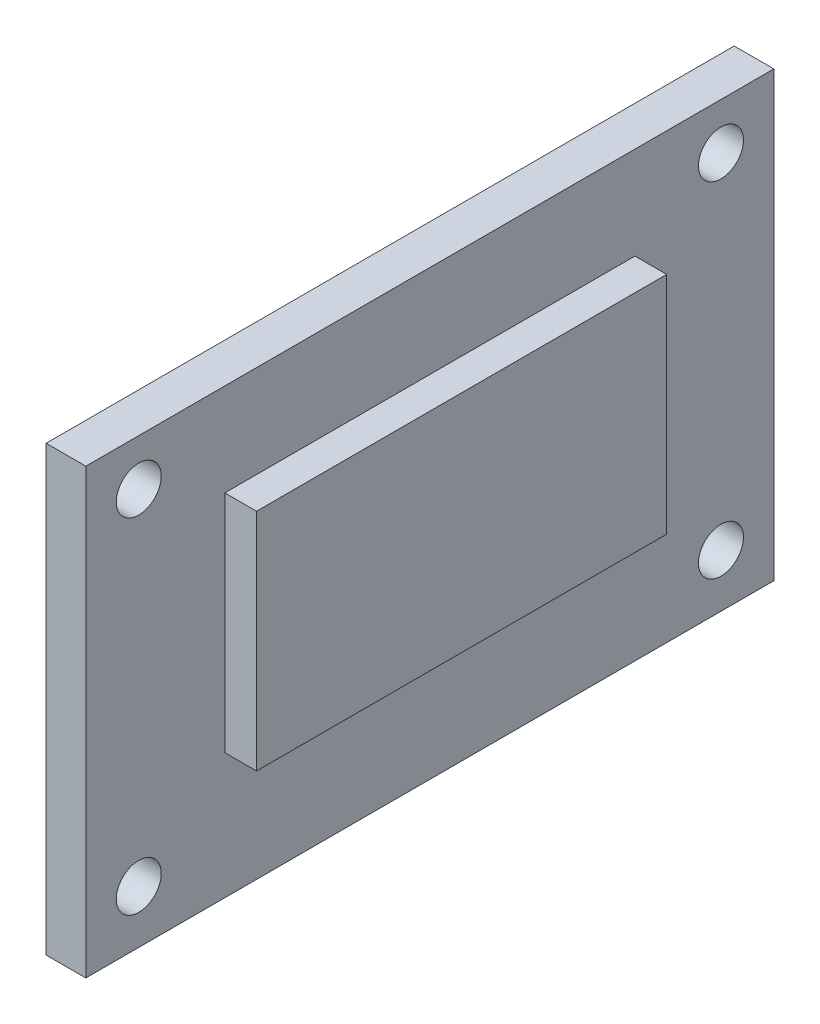
SolidWorks part; units mm, degrees
ref_plane "Front Plane" through (0, 0, 0) normal (0, 0, 1) x (1, 0, 0)
ref_plane "Top Plane" through (0, 0, 0) normal (0, 1, 0) x (1, 0, 0)
ref_plane "Right Plane" through (0, 0, 0) normal (1, 0, 0) x (0, 0, -1)
ref_plane "PXm75_4" through (-75.4, 0, 0) normal (1, 0, 0) x (0, 0, -1)
sketch "Sketch1" plane through (-75.4, 0, 0) normal (1, 0, 0) x (0, 0, -1)
  line L0 (-90, -27) -> (-38, -27)
  line L1 (-38, -27) -> (-38, 6.5)
  line L2 (-38, 6.5) -> (-90, 6.5)
  line L3 (-90, 6.5) -> (-90, -27)
extrude "Cover Plate" add sketch "Sketch1" along normal blind 3
ref_plane "PXm72_41" through (-72.41, 0, 0) normal (1, 0, 0) x (0, 0, -1)
sketch "Sketch2" plane through (-72.41, 0, 0) normal (1, 0, 0) x (0, 0, -1)
  line L0 (-79.5, -17.5) -> (-48.5, -17.5)
  line L1 (-48.5, -17.5) -> (-48.5, -0.5)
  line L2 (-48.5, -0.5) -> (-79.5, -0.5)
  line L3 (-79.5, -0.5) -> (-79.5, -17.5)
extrude "Locating Plug" add sketch "Sketch2" along normal blind 2.41
ref_plane "PXm76_4" through (-76.4, 0, 0) normal (1, 0, 0) x (0, 0, -1)
sketch "Sketch3" plane through (-76.4, 0, 0) normal (1, 0, 0) x (0, 0, -1)
  circle A0 centre (-86, -23) radius 1.7
  circle A1 centre (-86, 3) radius 1.7
  circle A2 centre (-42, -23) radius 1.7
  circle A3 centre (-42, 3) radius 1.7
extrude "Screw Holes" cut sketch "Sketch3" along normal blind 5
equation "\"BOARD_REAR\" = 86.0"
equation "\"BOARD_FRONT\" = 41.0"
equation "\"BOARD_END\" = 22.0"
equation "\"BOARD_ANGLED\" = 30.0"
equation "\"BOARD_DEPTH\" = 41.8431"
equation "\"PCB_T\" = 1.6"
equation "\"ABOVE_PCB\" = 14.0"
equation "\"BELOW_PCB\" = 6.0"
equation "\"MID_PARTS_H\" = 9.0"
equation "\"BOARD_HOLE_PILOT\" = 1.6"
equation "\"J2_X\" = 19.0"
equation "\"DUPONT_DROP\" = 14.0"
equation "\"BEND_R\" = 5.0"
equation "\"BOARD_GAP\" = 3.0"
equation "\"TOF_FOV\" = 25.0"
equation "\"TOF_MARGIN_DEG\" = 5.0"
equation "\"TOF_WIN_MARGIN\" = 1.0"
equation "\"TOF_Z\" = 9.0"
equation "\"TOF_SIDE_BEARING\" = 90.0"
equation "\"TOF_CONE_LEN\" = 70.0"
equation "\"CAM_W\" = 29.2"
equation "\"CAM_H\" = 28.2"
equation "\"CAM_D\" = 12.35"
equation "\"CAM_FRONT_Y\" = 43.0"
equation "\"CAM_BOTTOM_Z\" = 17.0"
equation "\"CAM_LENS_UP\" = 11.6"
equation "\"CAM_LENS_OPEN\" = 9.6"
equation "\"CAM_HFOV\" = 53.5"
equation "\"CAM_VFOV\" = 41.41"
equation "\"CAM_FOV_MARGIN\" = 3.0"
equation "\"CAM_FIT\" = 0.3"
equation "\"RIBBON_W\" = 16.0"
equation "\"RIBBON_T\" = 0.3"
equation "\"RIBBON_LEN\" = 150.0"
equation "\"RIBBON_EXIT_Y\" = 35.0"
equation "\"WALL\" = 2.4"
equation "\"HEAD_X\" = 48.4"
equation "\"HEAD_REAR_Y\" = -11.9"
equation "\"CAM_FOAM\" = 2.8"
equation "\"HEAD_FRONT_Y\" = 48.2"
equation "\"HEAD_TOP_Z\" = 50.6"
equation "\"HEAD_BOT_Z\" = -28.4"
equation "\"HEAD_SPLIT_Z\" = -4.0"
equation "\"SKIRT_T\" = 1.2"
equation "\"SKIRT_H\" = 3.0"
equation "\"SKIRT_FIT\" = 0.3"
equation "\"VISOR\" = 7.8"
equation "\"VISOR_Z\" = 40.0"
equation "\"ROOF_SLOPE_Y\" = 40.0"
equation "\"ROOF_CHAMFER\" = 10.0"
equation "\"REAR_CHAMFER\" = 10.0"
equation "\"CORNER_CHAMFER\" = 6.0"
equation "\"LOWER_SIDE_FACET\" = 6.0"
equation "\"LIGHTBAR_DEPTH\" = 1.0"
equation "\"HOOD_Z\" = 14.0"
equation "\"HOOD_L\" = 6.0"
equation "\"SIDE_HOOD_L\" = 4.0"
equation "\"INSERT_M3_D\" = 4.0"
equation "\"INSERT_M3_L\" = 6.0"
equation "\"M3_CLEAR\" = 3.4"
equation "\"M2_PILOT\" = 1.6"
equation "\"M25_PILOT\" = 2.2"
equation "\"BOX_X\" = 72.4"
equation "\"BOX_FRONT_Y\" = -11.9"
equation "\"BOX_REAR_Y\" = -154.4"
equation "\"BOX_BOT_Z\" = -28.4"
equation "\"BOX_TOP_Z\" = 10.0"
equation "\"LID_T\" = 2.4"
equation "\"LID_SKIRT\" = 1.6"
equation "\"LID_TONGUE_H\" = 3.0"
equation "\"LID_FIT\" = 0.3"
equation "\"GNSS_WIN_T\" = 1.2"
equation "\"DIVIDER_Y\" = -86.0"
equation "\"PI_X0\" = -40.0"
equation "\"PI_X1\" = 45.0"
equation "\"PI_Y1\" = -26.3"
equation "\"PI_Y0\" = -82.3"
equation "\"PI_STANDOFF\" = 8.0"
equation "\"ESP_X0\" = -46.0"
equation "\"ESP_Y0\" = -149.0"
equation "\"ESP_L\" = 75.0"
equation "\"ESP_W\" = 52.0"
equation "\"ESP_STANDOFF\" = 12.0"
equation "\"BOX_REAR_CHAMFER\" = 8.0"
equation "\"BOX_REAR_FACET\" = 4.0"
equation "\"VENT_UPSTAND\" = 3.0"
equation "\"TUBE_D\" = 22.2"
equation "\"TUBE_LINER\" = 1.0"
equation "\"MOUNT_Y\" = -70.0"
equation "\"RAIL_W\" = 30.0"
equation "\"RAIL_W2\" = 38.0"
equation "\"RAIL_H\" = 6.0"
equation "\"SLIDE\" = 0.3"
equation "\"STOP_T\" = 6.0"
equation "\"CLAMP_W\" = 40.0"
equation "\"CLAMP_HALF\" = 20.0"
equation "\"CLAMP_DROP\" = 12.0"
equation "\"CAP_T\" = 12.0"
equation "\"CLAMP_BOLT_OFF\" = 16.6"
equation "\"M5_INSERT_D\" = 6.4"
equation "\"M5_CLEAR\" = 5.5"
equation "\"LOCK_D\" = 3.3"
equation "\"POD_TILT_DEG\" = 0.0"
equation "\"PRINT_LIMIT\" = 180.0"
